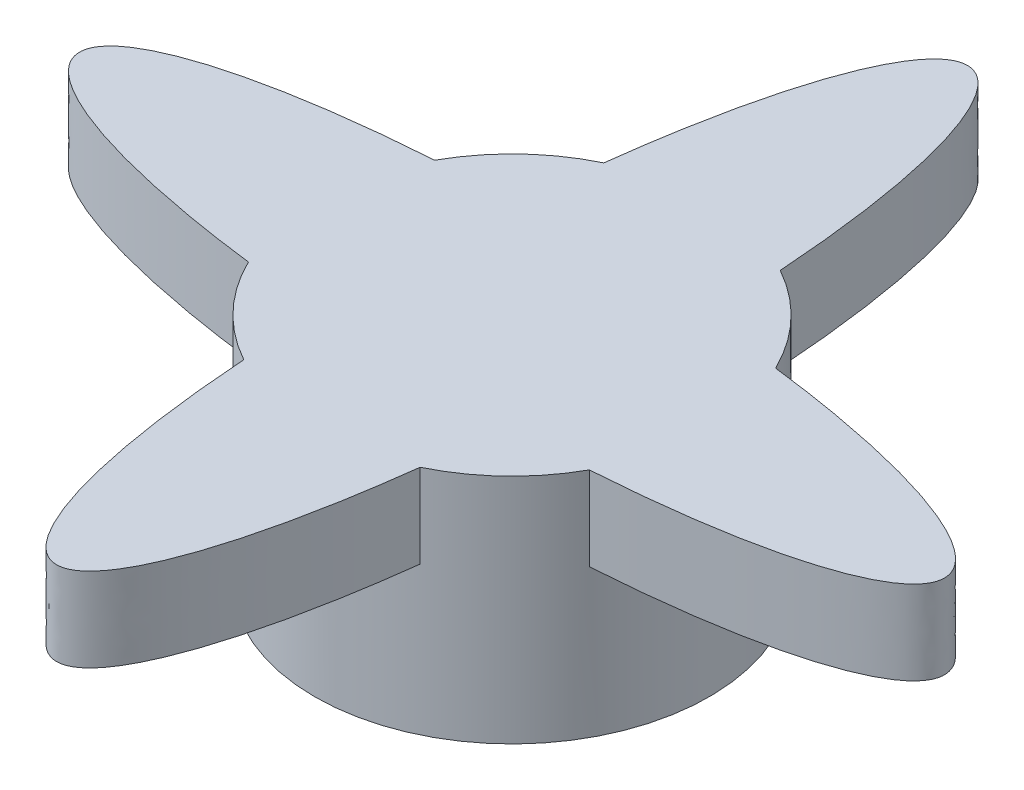
SolidWorks part; units mm, degrees
ref_plane "前视基准面" through (0, 0, 0) normal (0, 0, 1) x (1, 0, 0)
ref_plane "上视基准面" through (0, 0, 0) normal (0, 1, 0) x (1, 0, 0)
ref_plane "右视基准面" through (0, 0, 0) normal (1, 0, 0) x (0, 0, -1)
other "Configuration Table"
sketch "草图1" plane through (0, 0, 0) normal (0, 1, 0) x (1, 0, 0)
  circle A0 centre (0, 0) radius 2.5
  circle A1 centre (0, 0) radius 4
  dimension "D1" = 5
extrude "凸台-拉伸1" add sketch "草图1" along normal blind 3
sketch "草图2" plane through (0, 3, 0) normal (0, 1, 0) x (1, 0, 0)
  circle A1 centre (0, 0) radius 4
  circle A2 centre (0, 0) radius 4
  ellipse E0 centre (0, 0) end of major axis (-8.9966, 0.2459) minor radius 2 (3.5014, -1.9339) -> (3.6018, 1.7398) ccw
  ellipse E1 centre (0, 0) end of major axis (0.2459, 8.9966) minor radius 2 (-1.9339, -3.5014) -> (1.7398, -3.6018) ccw
  ellipse E2 centre (0, 0) end of major axis (8.9966, -0.2459) minor radius 2 (3.5014, -1.9339) -> (3.6018, 1.7398) ccw
  ellipse E3 centre (0, 0) end of major axis (-0.2459, -8.9966) minor radius 2 (-1.9339, -3.5014) -> (1.7398, -3.6018) ccw
  ellipse E4 centre (0, 0) end of major axis (0.2459, 8.9966) minor radius 2 (1.9339, 3.5014) -> (-1.7398, 3.6018) ccw
  ellipse E5 centre (0, 0) end of major axis (-0.2459, -8.9966) minor radius 2 (1.9339, 3.5014) -> (-1.7398, 3.6018) ccw
  ellipse E6 centre (0, 0) end of major axis (-8.9966, 0.2459) minor radius 2 (-3.5014, 1.9339) -> (-3.6018, -1.7398) ccw
  ellipse E7 centre (0, 0) end of major axis (8.9966, -0.2459) minor radius 2 (-3.5014, 1.9339) -> (-3.6018, -1.7398) ccw
  point P26 (0, 0)
  circle M4 centre (0, 0) radius 4
  dimension "D2" = 4
  dimension "D1" = 0
extrude "凸台-拉伸2" add sketch "草图2" along normal blind 1.7 contours E0 M4 | E4 M4 | E6 M4 | E1 M4 | A2
